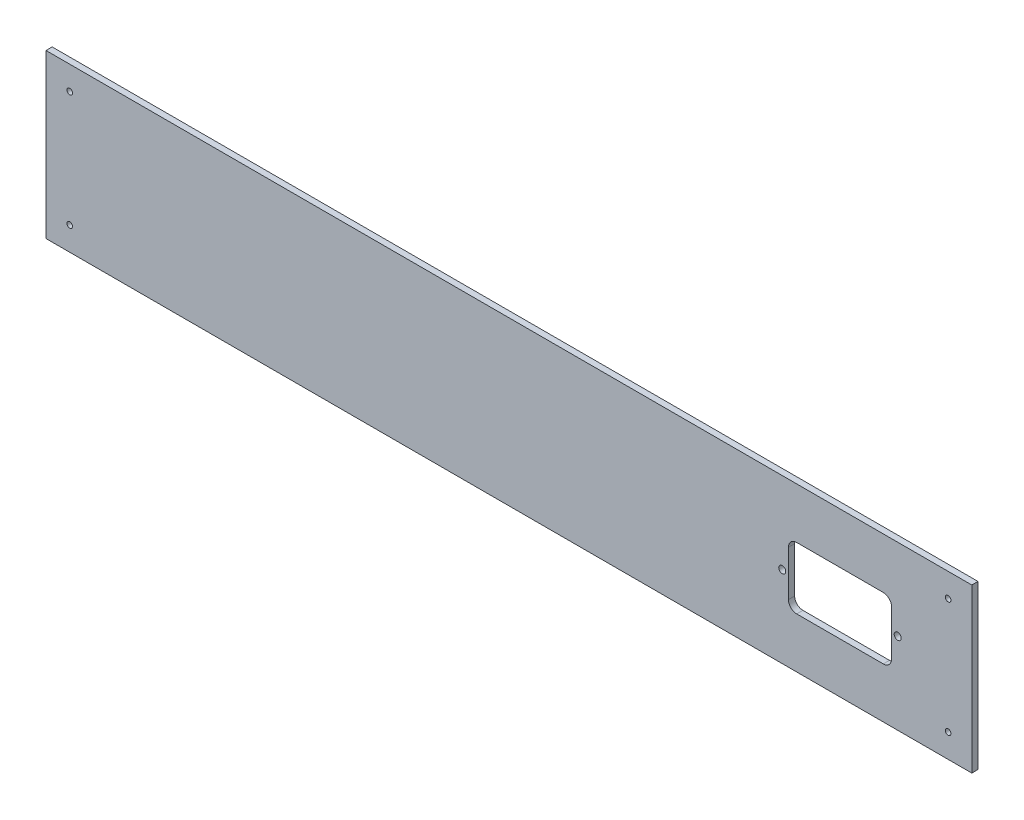
SolidWorks part; units mm, degrees
ref_plane "Piano frontale" through (0, 0, 0) normal (0, 0, 1) x (1, 0, 0)
ref_plane "Piano superiore" through (0, 0, 0) normal (0, 1, 0) x (1, 0, 0)
ref_plane "Piano destro" through (0, 0, 0) normal (1, 0, 0) x (0, 0, -1)
sketch "f" plane through (0, 0, 0) normal (0, 0, 1) x (1, 0, 0)
  line L0 (0, 0) -> (0, 79)
  line L1 (0, 79) -> (449, 79)
  line L2 (449, 79) -> (449, 0)
  line L3 (449, 0) -> (0, 0)
  line L4 (0, 39.5) -> (449, 39.5) construction
  line L5 (224.5, 42) -> (224.5, 123.488) construction
  line L10 (449, 79) -> (224.5, 0) construction
  line L11 (334, 39.5) -> (334, 81.5) construction
  line L12 (224.5, 0) -> (0, 79) construction
  line L13 (112.25, 42) -> (112.25, 84) construction
  circle A0 centre (11.5, 67.5) radius 1.3617
  circle A1 centre (437.5, 67.5) radius 1.3617
  circle A2 centre (11.5, 11.5) radius 1.3617
  circle A3 centre (437.5, 11.5) radius 1.3617
  dimension "D3" = 11.5
  dimension "D4" = 11.5
  dimension "D1" = 79
  dimension "D2" = 449
extrude "Estrusione-Estrusione1" add sketch "f" along normal blind 3
sketch "Sketch1" plane through (0, 0, 0) normal (0, 0, -1) x (-1, 0, 0)
  line L0 (0, 39.5) -> (-449, 39.5) construction
  line L1 (0, 79) -> (0, 0) construction
  line L2 (-449, 0) -> (-449, 79) construction
  line L7 (-364.0746, 54.3949) -> (-406.0746, 54.3949)
  line L8 (-360.0746, 50.3949) -> (-360.0746, 28.3949)
  line L9 (-364.0746, 24.3949) -> (-406.0746, 24.3949)
  line L10 (-410.0746, 50.3949) -> (-410.0746, 28.3949)
  arc A4 (-360.0746, 50.3949) -> (-364.0746, 54.3949) centre (-364.0746, 50.3949) ccw
  arc A5 (-360.0746, 28.3949) -> (-364.0746, 24.3949) centre (-364.0746, 28.3949) cw
  arc A6 (-406.0746, 24.3949) -> (-410.0746, 28.3949) centre (-406.0746, 28.3949) cw
  arc A7 (-410.0746, 50.3949) -> (-406.0746, 54.3949) centre (-406.0746, 50.3949) cw
  circle A8 centre (-413.0612, 39.5055) radius 1.7
  circle A9 centre (-357.0612, 39.5055) radius 1.7
extrude "Extrude1" cut sketch "Sketch1" against normal through all
